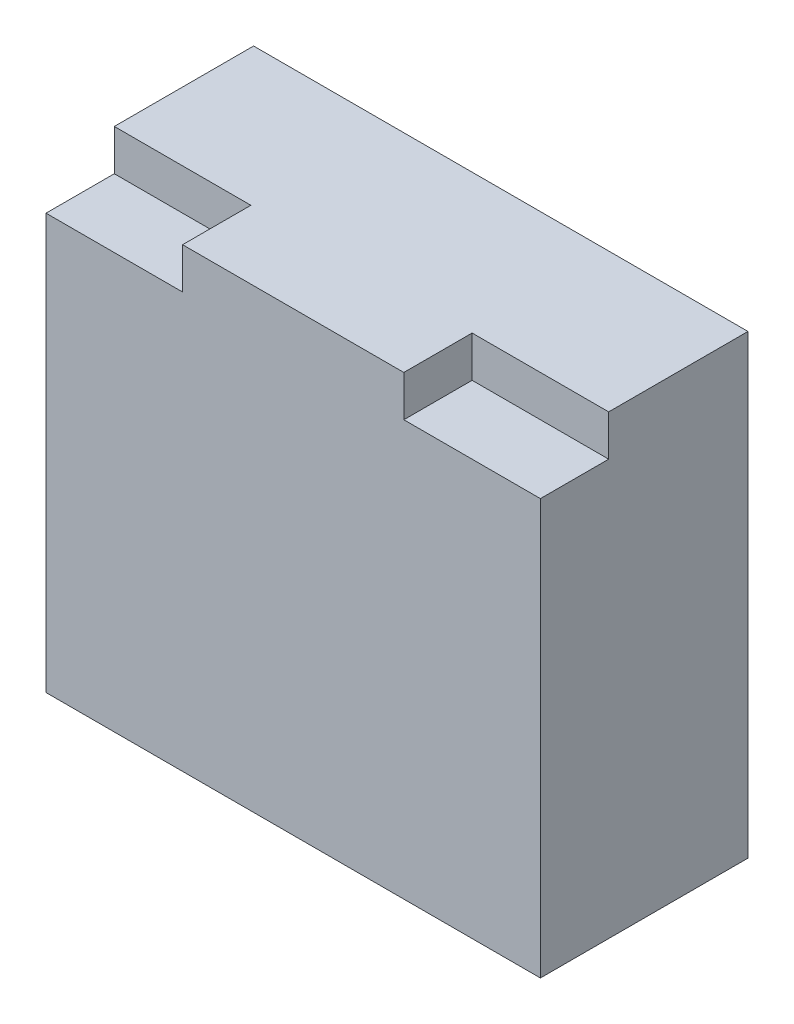
SolidWorks part; units mm, degrees
ref_plane "Front Plane" through (0, 0, 0) normal (0, 0, 1) x (1, 0, 0)
ref_plane "Top Plane" through (0, 0, 0) normal (0, 1, 0) x (1, 0, 0)
ref_plane "Right Plane" through (0, 0, 0) normal (1, 0, 0) x (0, 0, -1)
sketch "Sketch1" plane through (0, 0, 0) normal (0, 1, 0) x (1, 0, 0)
  line L1 (0, 0) -> (181, 0)
  line L2 (0, 0) -> (0, -76)
  line L3 (0, -76) -> (181, -76)
  line L4 (181, 0) -> (181, -76)
  dimension "D1" = 181
  dimension "D2" = 76
extrude "Boss-Extrude1" add sketch "Sketch1" along normal blind 167
sketch "Sketch3" plane through (0, 167, 0) normal (0, 1, 0) x (1, 0, 0)
  line L1 (181, -76) -> (131, -76)
  line L2 (181, -76) -> (181, -51)
  line L3 (181, -51) -> (131, -51)
  line L4 (131, -76) -> (131, -51)
  line L5 (0, -76) -> (50, -76)
  line L6 (0, -76) -> (0, -51)
  line L7 (0, -51) -> (50, -51)
  line L8 (50, -76) -> (50, -51)
  dimension "D1" = 25
  dimension "D2" = 50
extrude "Cut-Extrude2" cut sketch "Sketch3" against normal blind 15
